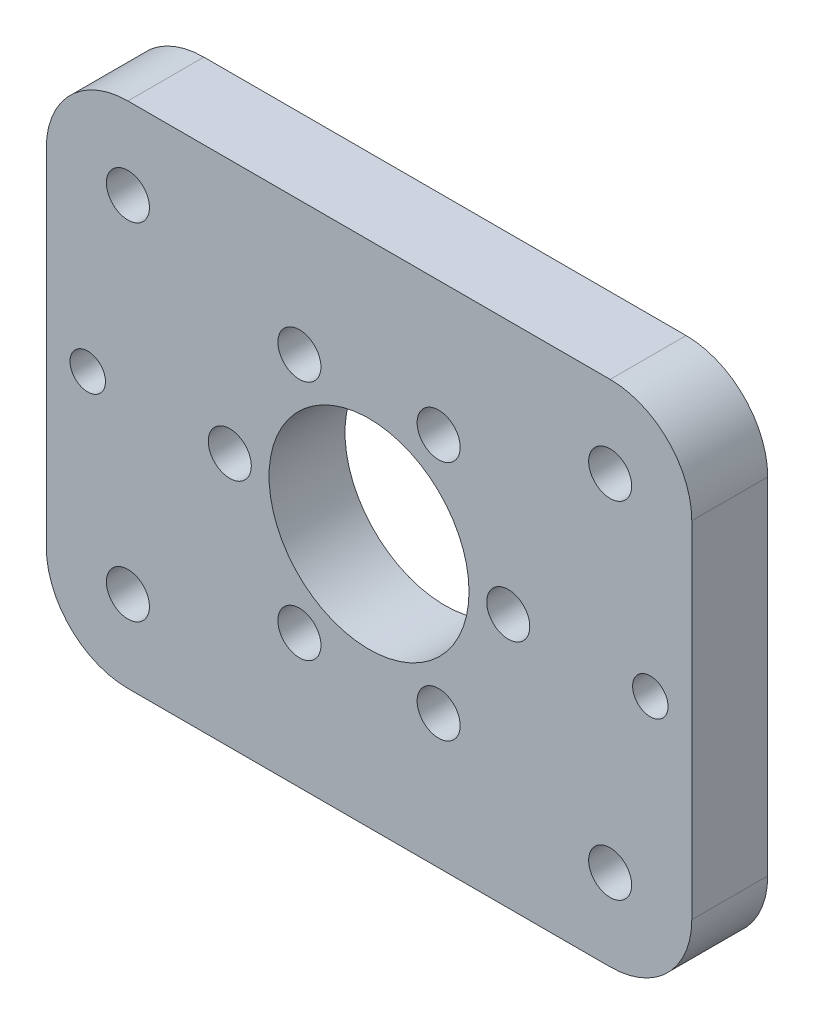
SolidWorks part; units mm, degrees
material "Balsa"
ref_plane "Front" through (0, 0, 0) normal (0, 0, 1) x (1, 0, 0)
ref_plane "Top" through (0, 0, 0) normal (0, 1, 0) x (1, 0, 0)
ref_plane "Right" through (0, 0, 0) normal (1, 0, 0) x (0, 0, -1)
sketch "Sketch1" plane through (0, 0, 0) normal (0, 0, 1) x (1, 0, 0)
  line L0 (25.4, 20) -> (-25.4, 20)
  line L1 (-25.4, 20) -> (-25.4, -20)
  line L2 (-25.4, -20) -> (25.4, -20)
  line L3 (0, 0) -> (0, 20) construction
  line L4 (25.4, 20) -> (25.4, -20)
  line L5 (0, 0) -> (-25.4, 0) construction
  circle A1 centre (0, 0) radius 8
  point P9 (0, -20)
  dimension "D1" = 16
  dimension "D2" = 40
  dimension "D3" = 25.4
extrude "Boss-Extrude1" add sketch "Sketch1" along normal blind 6
fillet "Fillet1" radius 6.35 4 edges at (-25.4, -20, 3) (25.4, -20, 3) (25.4, 20, 3) (-25.4, 20, 3)
sketch "Sketch8" plane through (0, 0, 6) normal (0, 0, 1) x (1, 0, 0)
  line L0 (-25.4, 0) -> (25.4, 0) construction
  line L1 (0, 0) -> (0, -22.225) construction
  line L3 (-25.4, 13.65) -> (-25.4, -13.65) construction
  line L6 (25.4, -13.65) -> (25.4, 13.65) construction
  line L7 (0, 0) -> (0, 20) construction
  line L8 (19.05, 20) -> (-19.05, 20) construction
  circle A0 centre (22.225, 0) radius 1.5
  circle A2 centre (-22.225, 0) radius 1.5
  circle A4 centre (0, 22.225) radius 1.5 [skipped]
  circle A5 centre (0, -22.225) radius 1.5 [skipped]
  dimension "D2" = 3
  dimension "D1" = 22.225
  dimension "D3" = 4
extrude "Cut-Extrude1" cut sketch "Sketch8" against normal through all
sketch "Sketch9" plane through (0, 0, 6) normal (0, 0, 1) x (1, 0, 0)
  line L0 (0, 0) -> (0, 20) construction
  line L1 (19.05, 20) -> (-19.05, 20) construction
  line L2 (0, 0) -> (-25.4, 0) construction
  line L3 (-25.4, 13.65) -> (-25.4, -13.65) construction
  line L4 (0, 0) -> (11, 0) construction
  line L5 (5.5, 9.5263) -> (0, 0) construction
  line L6 (0, 0) -> (-5.5, 9.5263) construction
  circle A0 centre (-19.05, 13.65) radius 1.8
  circle A1 centre (-19.05, -13.65) radius 1.8
  circle A2 centre (19.05, -13.65) radius 1.8
  circle A3 centre (19.05, 13.65) radius 1.8
  circle A4 centre (11, 0) radius 1.8
  circle A5 centre (5.5, -9.5263) radius 1.8
  circle A6 centre (-5.5, -9.5263) radius 1.8
  circle A7 centre (-11, 0) radius 1.8
  circle A8 centre (-5.5, 9.5263) radius 1.8
  circle A9 centre (5.5, 9.5263) radius 1.8
  dimension "D3" = 3.6
  dimension "D4" = 11
  dimension "D1" = 6.35
  dimension "D2" = 6.35
  dimension "D5" = 6
extrude "M3-through" cut sketch "Sketch9" against normal through all
other "Move Face2" face at (-25.4, 0, 3) face at (-22.8826, 17.4826, 3) face at (0, 20, 3) face at (22.8826, 17.4826, 3) face at (25.4, 0, 3) face at (0, -20, 3) face at (-20.85, -13.65, 0) face at (8, 0, 6) face at (23.725, 0, 0) face at (-20.725, 0, 0) face at (-17.25, 13.65, 0) face at (20.85, -13.65, 0) face at (17.25, 13.65, 0) face at (12.8, 0, 0) face at (7.3, -9.5263, 0) face at (-3.7, -9.5263, 0) face at (-9.2, 0, 0) face at (-3.7, 9.5263, 0) face at (7.3, 9.5263, 0) face at (-22.8826, -17.4826, 3) face at (22.8826, -17.4826, 3) parameters "D1"=0.1
